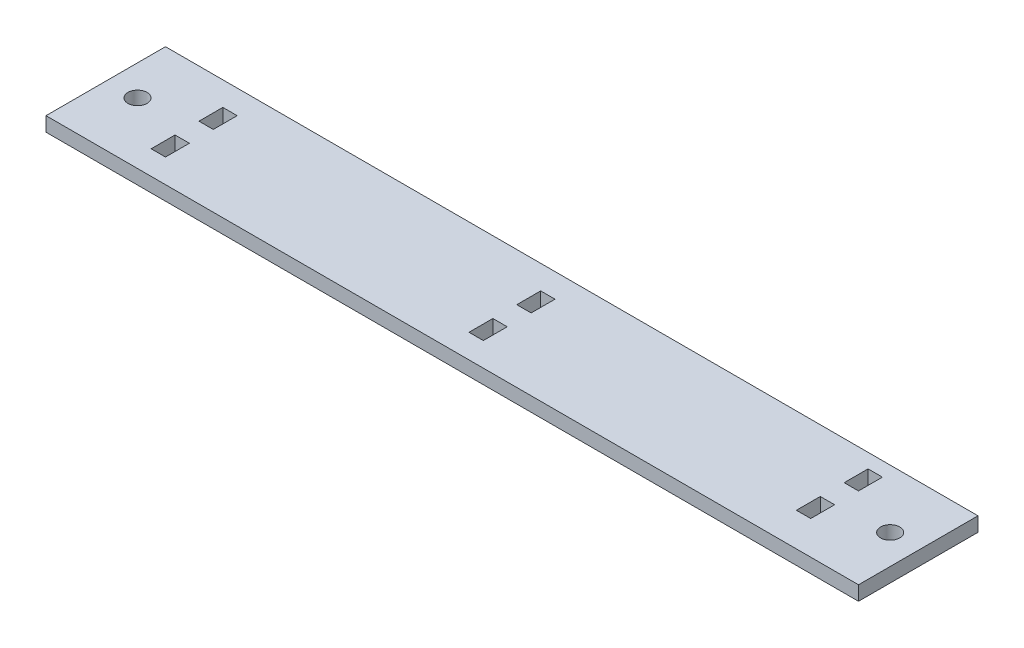
SolidWorks part; units mm, degrees
material "Buk"
ref_plane "Přední rovina" through (0, 0, 0) normal (0, 0, 1) x (1, 0, 0)
ref_plane "Horní rovina" through (0, 0, 0) normal (0, 1, 0) x (1, 0, 0)
ref_plane "Pravá rovina" through (0, 0, 0) normal (1, 0, 0) x (0, 0, -1)
sketch "Skica1" plane through (0, 0, 0) normal (0, 1, 0) x (1, 0, 0)
  line L0 (-85, -12.5) -> (85, 12.5) construction
  line L1 (-85, 12.5) -> (85, 12.5)
  line L2 (-85, 12.5) -> (-85, -12.5)
  line L3 (-85, -12.5) -> (85, -12.5)
  line L4 (85, 12.5) -> (85, -12.5)
  dimension "D1" = 170
  dimension "D2" = 25
extrude "Přidat vysunutím1" add sketch "Skica1" along normal blind 3
sketch "Skica2" plane through (0, 0, 0) normal (0, 1, 0) x (1, 0, 0)
  line L0 (1.5, 7.5) -> (-1.5, -7.5) construction
  line L1 (-1.5, 7.5) -> (1.5, 7.5)
  line L2 (-1.5, 7.5) -> (-1.5, 2.5)
  line L3 (-1.5, 2.5) -> (1.5, 2.5)
  line L4 (1.5, 7.5) -> (1.5, 2.5)
  line L5 (-1.5, -2.5) -> (1.5, -2.5)
  line L6 (-1.5, -2.5) -> (-1.5, -7.5)
  line L7 (-1.5, -7.5) -> (1.5, -7.5)
  line L8 (1.5, -2.5) -> (1.5, -7.5)
  line L9 (-68, 7.5) -> (-65, 7.5)
  line L10 (-68, 7.5) -> (-68, 2.5)
  line L11 (-68, 2.5) -> (-65, 2.5)
  line L12 (-65, 7.5) -> (-65, 2.5)
  line L13 (-68, -2.5) -> (-65, -2.5)
  line L14 (-68, -2.5) -> (-68, -7.5)
  line L15 (-68, -7.5) -> (-65, -7.5)
  line L16 (-65, -2.5) -> (-65, -7.5)
  line L17 (65, 9.5) -> (68, 9.5)
  line L18 (65, 9.5) -> (65, 4.5)
  line L19 (65, 4.5) -> (68, 4.5)
  line L20 (68, 9.5) -> (68, 4.5)
  line L21 (65, -0.5) -> (68, -0.5)
  line L22 (65, -0.5) -> (65, -5.5)
  line L23 (65, -5.5) -> (68, -5.5)
  line L24 (68, -0.5) -> (68, -5.5)
  line L25 (-1.5, 2.5) -> (-1.5, -2.5) construction
  line L26 (65, 4.5) -> (65, -0.5) construction
  line L27 (-65, 0) -> (65, 0) construction
  dimension "D1" = 130
  dimension "D3" = 3
  dimension "D4" = 5
  dimension "D5" = 5
  dimension "D6" = 2
extrude "Odebrat vysunutím2" cut sketch "Skica2" along normal through all
sketch "Skica3" plane through (0, 0, 0) normal (0, 1, 0) x (1, 0, 0)
  line L0 (-85, 12.5) -> (-85, -12.5) construction
  line L1 (85, 12.5) -> (-85, 12.5) construction
  circle A0 centre (-78.65, 0.29) radius 2
  circle A1 centre (78.83, 0.29) radius 2
  dimension "D1" = 6.35
  dimension "D2" = 4
  dimension "D3" = 157.48
  dimension "D4" = 12.21
extrude "Odebrat vysunutím3" cut sketch "Skica3" along normal through all
